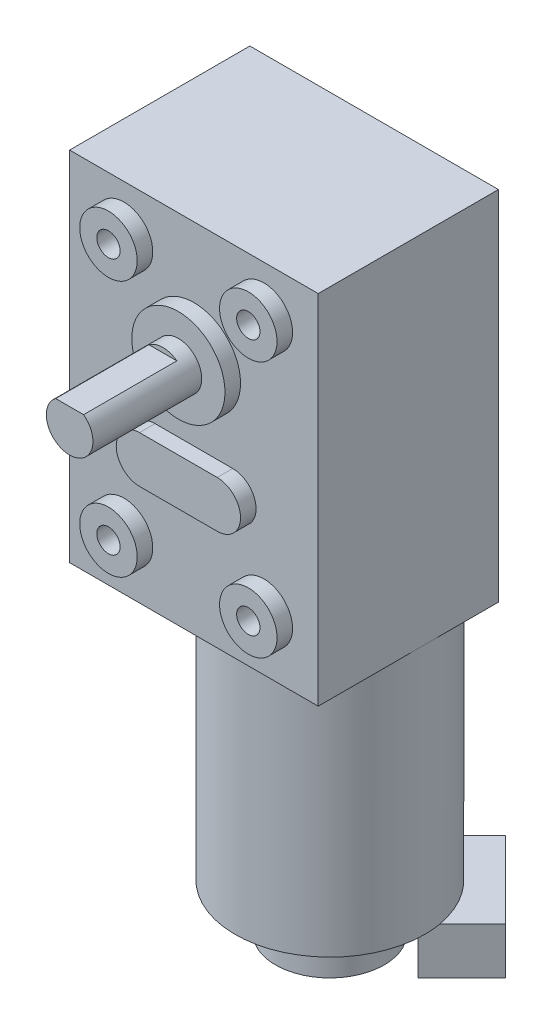
SolidWorks part; units mm, degrees
ref_plane "Спереди" through (0, 0, 0) normal (0, 0, 1) x (1, 0, 0)
ref_plane "Сверху" through (0, 0, 0) normal (0, 1, 0) x (1, 0, 0)
ref_plane "Справа" through (0, 0, 0) normal (1, 0, 0) x (0, 0, -1)
sketch "тело двигателя" plane through (0, 0, 0) normal (0, 0, 1) x (1, 0, 0)
  line L0 (0, 15) -> (0, -31) construction
  line L1 (-16, 15) -> (16, 15)
  line L2 (-16, 15) -> (-16, -31)
  line L3 (-16, -31) -> (16, -31)
  line L4 (16, 15) -> (16, -31)
  line L5 (-16, 0) -> (16, 0) construction
  point P9 (0, 0)
  dimension "осьКрай" = 15
  dimension "двигательW" = 32
  dimension "двигательH" = 46
extrude "корпус редуктора" add sketch "тело двигателя" along normal blind 23.2
sketch "Эскиз1" plane through (0, -31, 0) normal (0, -1, 0) x (1, 0, 0)
  line L0 (16, 23.2) -> (16, 0) construction
  line L1 (-16, 23.2) -> (16, 23.2) construction
  circle A0 centre (3.8, 9.5) radius 12.2
  dimension "диаметр цилиндра" = 24.4
  dimension "отступ" = 13.7
extrude "корпус двигателя" add sketch "Эскиз1" along normal blind 30.8
sketch "наплывы шурупов" plane through (0, 0, 23.2) normal (0, 0, 1) x (1, 0, 0)
  line L0 (-9, 9) -> (-9, -24) construction
  line L1 (-9, -24) -> (9, -24) construction
  line L2 (9, -24) -> (9, 9) construction
  line L3 (9, 9) -> (-9, 9) construction
  line L4 (0, 15) -> (0, -31) construction
  line L5 (16, 15) -> (-16, 15) construction
  line L6 (-16, -31) -> (16, -31) construction
  circle A0 centre (-9, 9) radius 3.7
  circle A1 centre (9, 9) radius 3.7
  circle A2 centre (9, -24) radius 3.7
  circle A3 centre (-9, -24) radius 3.7
  point P10 (0, 9)
  dimension "D4" = 7.4
  dimension "D1" = 18
  dimension "D2" = 33
  dimension "D3" = 6
sketch "наплыв оси" plane through (0, 0, 23.2) normal (0, 0, 1) x (1, 0, 0)
  line L0 (0, 15) -> (0, -31) construction
  line L1 (16, 15) -> (-16, 15) construction
  circle A0 centre (0, 0) radius 6
  dimension "диаметр наплыва" = 12
  dimension "положение наплыва" = 15
sketch "овал" plane through (0, 0, 23.2) normal (0, 0, 1) x (1, 0, 0)
  line L0 (-5, -10) -> (5, -10)
  line L1 (-5, -16) -> (5, -16)
  line L2 (-8, -13) -> (8, -13) construction
  line L3 (0, 15) -> (0, -31) construction
  line L4 (16, 15) -> (-16, 15) construction
  arc A0 (-5, -10) -> (-5, -16) centre (-5, -13) ccw
  arc A1 (5, -16) -> (5, -10) centre (5, -13) ccw
  point P8 (0, -13)
  dimension "D1" = 6
  dimension "отступ овала" = 28
  dimension "D2" = 16
extrude "наплывы винтов" add sketch "наплывы шурупов" along normal blind 2
extrude "наплыв под осью" add sketch "наплыв оси" along normal blind 2
extrude "наплыв овал" add sketch "овал" along normal blind 2
sketch "Эскиз6" plane through (0, 0, 25.2) normal (0, 0, 1) x (1, 0, 0)
  circle A0 centre (0, 0) radius 3
  dimension "диаметр оси" = 6
extrude "ось двигателя" add sketch "Эскиз6" along normal blind 14
sketch "d-вал" plane through (0, 0, 39.2) normal (0, 0, 1) x (1, 0, 0)
  line L0 (-1.8, 2.4) -> (1.8, 2.4)
  arc A1 (-1.8, 2.4) -> (1.8, 2.4) centre (0, 0) cw
  circle A4 centre (0, 0) radius 3 construction
  dimension "D1" = 2.4
extrude "срез вала" cut sketch "d-вал" against normal blind 12
sketch "винты" plane through (0, 0, 25.2) normal (0, 0, 1) x (1, 0, 0)
  circle A0 centre (9, 9) radius 1.5
  circle A1 centre (9, -24) radius 1.5
  circle A2 centre (-9, 9) radius 1.5
  circle A3 centre (-9, -24) radius 1.5
  dimension "диаметр под винт" = 3
extrude "отверстия под винты" cut sketch "винты" against normal blind 5
sketch "диаметр платы" plane through (0, -61.8, 0) normal (0, -1, 0) x (1, 0, 0)
  circle A0 centre (3.8, 9.5) radius 12.2
extrude "плата энкодера" add sketch "диаметр платы" along normal blind 1.5
sketch "Эскиз10" plane through (0, -63.3, 0) normal (0, -1, 0) x (1, 0, 0)
  circle A0 centre (3.8, 9.5) radius 7
  dimension "диаметр энкодера" = 14
extrude "энкодер" add sketch "Эскиз10" along normal blind 6
sketch "разъем энк" plane through (0, -63.3, 0) normal (0, -1, 0) x (1, 0, 0)
  line L0 (14.4066, 8.7929) -> (20.0635, 3.136)
  line L1 (14.4066, 8.7929) -> (4.5071, -1.1066)
  line L2 (20.0635, 3.136) -> (10.164, -6.7635)
  line L3 (4.5071, -1.1066) -> (10.164, -6.7635)
  line L4 (7.3355, -3.935) -> (17.235, 5.9645) construction
  line L5 (9.4569, 3.8431) -> (15.1137, -1.8137) construction
  line L6 (3.8, 9.5) -> (12.2853, 1.0147) construction
  line L7 (-8.4, 9.5) -> (16, 9.5) construction
  circle A0 centre (3.8, 9.5) radius 12.2 construction
  arc A3 (16, 9.5) -> (-3.8544, 0) centre (3.8, 9.5) ccw construction
  dimension "D1" = 14
  dimension "D2" = 8
  dimension "D3" = 45
  dimension "D4" = 12
extrude "разъем энкодера" add sketch "разъем энк" along normal blind 6
